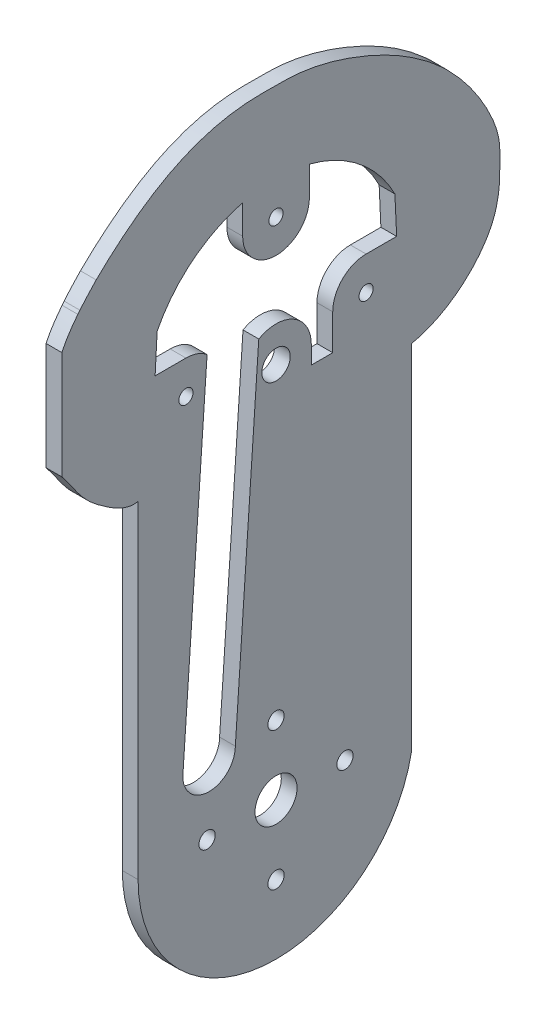
SolidWorks part; units mm, degrees
ref_plane "Plan de face" through (0, 0, 0) normal (0, 0, 1) x (1, 0, 0)
ref_plane "Plan de dessus" through (0, 0, 0) normal (0, 1, 0) x (1, 0, 0)
ref_plane "Plan de droite" through (0, 0, 0) normal (1, 0, 0) x (0, 0, -1)
sketch "Esquisse1" plane through (0, 0, 0) normal (1, 0, 0) x (0, 0, -1)
  line L19 (-6.1849, 6.1035) -> (-6.1849, 11.6469)
  line L20 (6.5151, 6.1035) -> (6.5151, 11.6469)
  line L21 (-10.6299, -14.9225) -> (-10.6299, -21.6694)
  line L22 (-16.9799, -8.5725) -> (-22.849, -8.5725)
  line L23 (17.3101, -8.5725) -> (23.1259, -8.5725)
  line L24 (-40.6082, -16.1449) -> (-40.6083, -16.3483)
  line L25 (0.1651, -90) -> (0.1651, -116.2575) construction
  line L26 (10.9601, -14.9225) -> (10.9601, -21.6694)
  line L27 (0.1651, 0) -> (0.1651, -90) construction
  line L28 (-26.0924, -27.6543) -> (-26.0924, -90) construction
  line L29 (10.9601, -21.6694) -> (6.8802, -21.6694)
  line L30 (6.8802, -21.6694) -> (6.8802, -18.2245)
  line L31 (-6.55, -18.2245) -> (-6.55, -21.6694)
  line L32 (-6.55, -21.6694) -> (-10.6299, -21.6694)
  line L33 (-26.0924, -90) -> (25.954, -90) construction
  line L34 (25.954, -90) -> (25.954, -27.6542) construction
  line L35 (-40.6082, 4.1425) -> (-40.6082, -12.7)
  line L36 (-26.0924, -27.6543) -> (-26.0924, -90)
  line L37 (25.954, -27.6542) -> (25.954, -90)
  line L38 (-40.6082, -16.1449) -> (-40.6082, -12.7)
  line L39 (-37.9035, 8.4934) -> (-36.4387, 10.3053) construction
  line L40 (-22.4631, -1.4086) -> (-22.849, -8.5725)
  line L41 (22.7933, -1.4086) -> (23.1259, -8.5725)
  circle A4 centre (-16.9799, -14.9225) radius 1.3525
  arc A5 (22.7933, -1.4086) -> (6.5151, 11.6469) centre (0.1651, -12.9465) ccw
  arc A6 (6.8802, -18.2245) -> (-6.55, -18.2245) centre (0.1651, -18.2245) ccw
  arc A7 (-37.1666, 9.4049) -> (-37.5578, 8.9143) centre (-0.9364, -19.8843) ccw
  circle A8 centre (0.1651, -18.2245) radius 2.7051
  circle A9 centre (17.3101, -14.9225) radius 1.3525
  circle A10 centre (0.1651, 6.1035) radius 1.3525
  arc A11 (-6.1849, 6.1035) -> (6.5151, 6.1035) centre (0.1651, 6.1035) ccw
  arc A12 (-6.1849, 11.6469) -> (-22.4631, -1.4086) centre (0.1651, -12.9465) ccw
  arc A13 (-10.6299, -14.9225) -> (-16.9799, -8.5725) centre (-16.9799, -14.9225) ccw
  arc A14 (-26.0924, -90) -> (25.954, -85.0614) centre (0.1651, -90) ccw
  arc A15 (17.3101, -8.5725) -> (10.9601, -14.9225) centre (17.3101, -14.9225) ccw
  circle A16 centre (0.1651, -103.1288) radius 1.55
  circle A17 centre (-12.9637, -90) radius 1.55
  circle A18 centre (0.1651, -76.8712) radius 1.55
  circle A19 centre (13.2939, -90) radius 1.55
  circle A20 centre (0.1651, -90) radius 4
  spline S5 degree 3 poles (31.4351, 15.2777) (30.2997, 16.3094) (29.1137, 17.2754) (26.6466, 19.0843) (25.3605, 19.9283) (21.4323, 22.2657) (18.7017, 23.5637) (14.4778, 25.2131) (13.0492, 25.7149) (10.8644, 26.3699) (10.1291, 26.5718) (8.6416, 26.9365) (7.8908, 27.0988) (5.638, 27.5124) (4.1274, 27.6937) (2.2253, 27.7687) (1.8441, 27.7755) (1.0809, 27.78) (0.6989, 27.7774) (-0.4463, 27.7791) (-1.2089, 27.7978) (-2.7327, 27.8153) (-3.4921, 27.8063) (-5.0041, 27.74) (-5.757, 27.6849) (-8.0062, 27.4518) (-9.4927, 27.2046) (-11.702, 26.6888) (-12.4349, 26.4915) (-13.8943, 26.0519) (-14.6221, 25.8075) (-16.7654, 25.0122) (-18.1515, 24.4005) (-20.8478, 23.0325) (-22.1587, 22.2775) (-24.7165, 20.6454) (-25.9664, 19.7652) (-28.3913, 17.9197) (-29.5674, 16.9543) (-31.2876, 15.4541) (-31.8538, 14.9457) (-32.9728, 13.9129) (-33.5258, 13.3888) (-34.0661, 12.8498) knots 0 0 0 0 0.0625 0.0625 0.125 0.125 0.25 0.25 0.3125 0.3125 0.34375 0.34375 0.375 0.375 0.4375 0.4375 0.453125 0.453125 0.46875 0.46875 0.5 0.5 0.53125 0.53125 0.5625 0.5625 0.625 0.625 0.65625 0.65625 0.6875 0.6875 0.75 0.75 0.8125 0.8125 0.875 0.875 0.9375 0.9375 0.96875 0.96875 1 1 1 1
  spline S6 degree 3 poles (-40.6083, -16.3483) (-40.3656, -16.6612) (-40.1123, -16.9655) (-39.6302, -17.5937) (-39.4007, -17.9172) (-38.719, -18.8931) (-38.2719, -19.5496) (-37.3385, -20.831) (-36.8555, -21.4585) (-36.0597, -22.3425) (-35.7819, -22.627) (-35.2029, -23.1772) (-34.9007, -23.4435) (-33.9719, -24.2127) (-33.3244, -24.6854) (-32.0108, -25.6045) (-31.3481, -26.0558) (-30.3031, -26.6606) (-29.9483, -26.8487) (-29.2225, -27.185) (-28.8514, -27.3338) (-28.0836, -27.5707) (-27.6853, -27.658) (-27.0907, -27.7154) (-26.8919, -27.7226) (-26.5928, -27.7129) (-26.493, -27.7063) (-26.293, -27.6856) (-26.1927, -27.6705) (-26.0924, -27.6543) knots 0 0 0 0 0.0625 0.0625 0.125 0.125 0.25 0.25 0.375 0.375 0.4375 0.4375 0.5 0.5 0.625 0.625 0.75 0.75 0.8125 0.8125 0.875 0.875 0.9375 0.9375 0.96875 0.96875 0.984375 0.984375 1 1 1 1
  spline S7 degree 3 poles (25.954, -27.6542) (27.1791, -27.4195) (28.3534, -27.0518) (30.0571, -26.3492) (30.6151, -26.0893) (31.7129, -25.5214) (32.2545, -25.2121) (33.8272, -24.2304) (34.814, -23.5021) (36.672, -21.9072) (37.5433, -21.0408) (38.7519, -19.6235) (39.1347, -19.135) (39.851, -18.1314) (40.1855, -17.6153) (40.8014, -16.5506) (41.0826, -16.002) (41.457, -15.1502) (41.5742, -14.8604) (41.7897, -14.2771) (41.888, -13.9835) (42.3347, -12.5068) (42.5462, -11.2963) (42.7176, -9.4515) (42.7506, -8.8307) (42.7729, -7.9005) (42.7754, -7.5904) (42.7756, -6.9702) (42.7721, -6.6601) (42.7721, -6.35) knots 0 0 0 0 0.125 0.125 0.1875 0.1875 0.25 0.25 0.375 0.375 0.5 0.5 0.5625 0.5625 0.625 0.625 0.6875 0.6875 0.71875 0.71875 0.75 0.75 0.875 0.875 0.9375 0.9375 0.96875 0.96875 1 1 1 1
  spline S8 degree 3 poles (42.7721, -6.35) (42.7721, -5.8749) (42.7838, -5.3981) (42.7897, -4.447) (42.7819, -3.973) (42.6725, -2.5632) (42.4992, -1.6375) (42.1063, -0.2679) (41.9541, 0.1856) (41.6148, 1.0877) (41.4301, 1.5303) (40.8449, 2.8393) (40.4166, 3.6895) (39.0468, 6.1905) (38.0131, 7.7873) (36.2917, 10.0821) (35.6885, 10.8307) (34.4365, 12.2817) (33.7862, 12.9857) (33.1121, 13.6686) knots 0 0 0 0 0.0625 0.0625 0.125 0.125 0.25 0.25 0.3125 0.3125 0.375 0.375 0.5 0.5 0.75 0.75 0.875 0.875 1 1 1 1
  spline S9 degree 3 poles (-37.5578, 8.9143) (-38.1429, 8.1702) (-38.7095, 7.4127) (-39.7419, 5.8248) (-40.2031, 4.9988) (-40.6082, 4.1425) knots 0 0 0 0 0.5 0.5 1 1 1 1
  spline S10 degree 3 poles (-34.0661, 12.8498) (-35.1598, 11.6922) (-36.2511, 10.5374) (-37.1666, 9.4049) knots 0 0 0 0 1 1 1 1
  spline S11 degree 2 poles (33.1121, 13.6686) (32.3322, 14.5391) (31.4351, 15.2777) knots 0 0 0 1 1 1
  point P69 (0.1651, -90)
  dimension "D2" = 4
  dimension "D3" = 8
  dimension "D4" = 3.1
  dimension "D1" = 90
sketch "Esquisse3" plane through (0, 0, 0) normal (1, 0, 0) x (0, 0, -1)
  line L0 (-6.1849, 6.1035) -> (-6.1849, 11.6469)
  line L1 (6.5151, 6.1035) -> (6.5151, 11.6469)
  line L3 (-16.9799, -8.5725) -> (-22.849, -8.5725)
  line L4 (17.3101, -8.5725) -> (23.1259, -8.5725)
  line L5 (-40.6082, -16.1449) -> (-40.6083, -16.3483)
  line L6 (0.1651, -90) -> (0.1651, -116.2575) construction
  line L7 (10.9601, -14.9225) -> (10.9601, -21.6694)
  line L8 (0.1651, 0) -> (0.1651, -90) construction
  line L9 (-26.0924, -27.6543) -> (-26.0924, -90) construction
  line L10 (10.9601, -21.6694) -> (6.8802, -21.6694)
  line L11 (6.8802, -21.6694) -> (6.8802, -18.2245)
  line L14 (-26.0924, -90) -> (25.954, -90) construction
  line L15 (25.954, -90) -> (25.954, -27.6542) construction
  line L16 (-40.6082, 4.1425) -> (-40.6082, -12.7)
  line L17 (-26.0924, -27.6543) -> (-26.0924, -90)
  line L18 (25.954, -27.6542) -> (25.954, -94.9386)
  line L19 (-40.6082, -16.1449) -> (-40.6082, -12.7)
  line L21 (-22.4631, -1.4086) -> (-22.849, -8.5725)
  line L22 (22.7933, -1.4086) -> (23.1259, -8.5725)
  line L23 (0.1651, -76.8533) -> (-12.9562, -90) construction
  line L24 (-6.3955, -83.4266) -> (-18.7628, -71.0833) construction
  line L25 (0.1651, -18.2245) -> (-16.9799, -14.9225) construction
  line L26 (-12.5792, -77.255) -> (-8.4074, -16.5735) construction
  line L27 (-10.4933, -46.9142) -> (-15.4698, -46.5721) construction
  line L28 (-17.5321, -76.5707) -> (-12.9562, -10.0101)
  line L29 (-7.5792, -77.255) -> (-3.1182, -12.3668)
  circle A0 centre (-16.9799, -14.9225) radius 1.3525
  arc A1 (22.7933, -1.4086) -> (6.5151, 11.6469) centre (0.1651, -12.9465) ccw
  arc A2 (6.8802, -18.2245) -> (-3.1182, -12.3668) centre (0.1651, -18.2245) ccw
  arc A3 (-37.1666, 9.4049) -> (-37.5578, 8.9143) centre (-0.9364, -19.8843) ccw
  circle A4 centre (0.1651, -18.2245) radius 2.7051
  circle A5 centre (17.3101, -14.9225) radius 1.3525
  circle A6 centre (0.1651, 6.1035) radius 1.3525
  arc A7 (-6.1849, 6.1035) -> (6.5151, 6.1035) centre (0.1651, 6.1035) ccw
  arc A8 (-6.1849, 11.6469) -> (-22.4631, -1.4086) centre (0.1651, -12.9465) ccw
  arc A9 (-12.9562, -10.0101) -> (-16.9799, -8.5725) centre (-16.9799, -14.9225) ccw
  arc A10 (-26.0924, -90) -> (25.954, -94.9386) centre (0.1651, -90) ccw
  arc A11 (17.3101, -8.5725) -> (10.9601, -14.9225) centre (17.3101, -14.9225) ccw
  circle A12 centre (0.1651, -103.1288) radius 1.55
  circle A13 centre (-12.9562, -90) radius 1.55
  circle A14 centre (0.1651, -76.8533) radius 1.55
  circle A15 centre (13.2939, -90) radius 1.55
  circle A16 centre (0.1651, -90) radius 4
  circle A17 centre (0.1651, -90) radius 26.2575 construction
  arc A18 (-17.5321, -76.5707) -> (-7.5792, -77.255) centre (-12.5792, -77.255) ccw
  spline S0 degree 3 poles (31.4351, 15.2777) (30.2997, 16.3094) (29.1137, 17.2754) (26.6466, 19.0843) (25.3605, 19.9283) (21.4323, 22.2657) (18.7017, 23.5637) (14.4778, 25.2131) (13.0492, 25.7149) (10.8644, 26.3699) (10.1291, 26.5718) (8.6416, 26.9365) (7.8908, 27.0988) (5.638, 27.5124) (4.1274, 27.6937) (2.2253, 27.7687) (1.8441, 27.7755) (1.0809, 27.78) (0.6989, 27.7774) (-0.4463, 27.7791) (-1.2089, 27.7978) (-2.7327, 27.8153) (-3.4921, 27.8063) (-5.0041, 27.74) (-5.757, 27.6849) (-8.0062, 27.4518) (-9.4927, 27.2046) (-11.702, 26.6888) (-12.4349, 26.4915) (-13.8943, 26.0519) (-14.6221, 25.8075) (-16.7654, 25.0122) (-18.1515, 24.4005) (-20.8478, 23.0325) (-22.1587, 22.2775) (-24.7165, 20.6454) (-25.9664, 19.7652) (-28.3913, 17.9197) (-29.5674, 16.9543) (-31.2876, 15.4541) (-31.8538, 14.9457) (-32.9728, 13.9129) (-33.5258, 13.3888) (-34.0661, 12.8498) knots 0 0 0 0 0.0625 0.0625 0.125 0.125 0.25 0.25 0.3125 0.3125 0.34375 0.34375 0.375 0.375 0.4375 0.4375 0.453125 0.453125 0.46875 0.46875 0.5 0.5 0.53125 0.53125 0.5625 0.5625 0.625 0.625 0.65625 0.65625 0.6875 0.6875 0.75 0.75 0.8125 0.8125 0.875 0.875 0.9375 0.9375 0.96875 0.96875 1 1 1 1
  spline S1 degree 3 poles (-40.6082, -16.3483) (-40.3656, -16.6612) (-40.1123, -16.9655) (-39.6302, -17.5937) (-39.4007, -17.9172) (-38.719, -18.8931) (-38.2719, -19.5496) (-37.3385, -20.831) (-36.8555, -21.4585) (-36.0597, -22.3425) (-35.7819, -22.627) (-35.2029, -23.1772) (-34.9007, -23.4435) (-33.9719, -24.2127) (-33.3244, -24.6854) (-32.0108, -25.6045) (-31.3481, -26.0558) (-30.3031, -26.6606) (-29.9483, -26.8487) (-29.2225, -27.185) (-28.8514, -27.3338) (-28.0836, -27.5707) (-27.6853, -27.658) (-27.0907, -27.7154) (-26.8919, -27.7226) (-26.5928, -27.7129) (-26.493, -27.7063) (-26.293, -27.6856) (-26.1927, -27.6705) (-26.0924, -27.6543) knots 0 0 0 0 0.0625 0.0625 0.125 0.125 0.25 0.25 0.375 0.375 0.4375 0.4375 0.5 0.5 0.625 0.625 0.75 0.75 0.8125 0.8125 0.875 0.875 0.9375 0.9375 0.96875 0.96875 0.984375 0.984375 1 1 1 1
  spline S2 degree 3 poles (25.954, -27.6542) (27.1791, -27.4195) (28.3534, -27.0518) (30.0571, -26.3492) (30.6151, -26.0893) (31.7129, -25.5214) (32.2545, -25.2121) (33.8272, -24.2304) (34.814, -23.5021) (36.672, -21.9072) (37.5433, -21.0408) (38.7519, -19.6235) (39.1347, -19.135) (39.851, -18.1314) (40.1855, -17.6153) (40.8014, -16.5506) (41.0826, -16.002) (41.457, -15.1502) (41.5742, -14.8604) (41.7897, -14.2771) (41.888, -13.9835) (42.3347, -12.5068) (42.5462, -11.2963) (42.7176, -9.4515) (42.7506, -8.8307) (42.7729, -7.9005) (42.7754, -7.5904) (42.7756, -6.9702) (42.7721, -6.6601) (42.7721, -6.35) knots 0 0 0 0 0.125 0.125 0.1875 0.1875 0.25 0.25 0.375 0.375 0.5 0.5 0.5625 0.5625 0.625 0.625 0.6875 0.6875 0.71875 0.71875 0.75 0.75 0.875 0.875 0.9375 0.9375 0.96875 0.96875 1 1 1 1
  spline S3 degree 3 poles (42.7721, -6.35) (42.7721, -5.8749) (42.7838, -5.3981) (42.7897, -4.447) (42.7819, -3.973) (42.6725, -2.5632) (42.4992, -1.6375) (42.1063, -0.2679) (41.9541, 0.1856) (41.6148, 1.0877) (41.4301, 1.5303) (40.8449, 2.8393) (40.4166, 3.6895) (39.0468, 6.1905) (38.0131, 7.7873) (36.2917, 10.0821) (35.6885, 10.8307) (34.4365, 12.2817) (33.7862, 12.9857) (33.1121, 13.6686) knots 0 0 0 0 0.0625 0.0625 0.125 0.125 0.25 0.25 0.3125 0.3125 0.375 0.375 0.5 0.5 0.75 0.75 0.875 0.875 1 1 1 1
  spline S4 degree 3 poles (-37.5578, 8.9143) (-38.1429, 8.1702) (-38.7095, 7.4127) (-39.7419, 5.8248) (-40.2031, 4.9988) (-40.6082, 4.1425) knots 0 0 0 0 0.5 0.5 1 1 1 1
  spline S5 degree 3 poles (-34.0661, 12.8498) (-35.1598, 11.6922) (-36.2511, 10.5374) (-37.1666, 9.4049) knots 0 0 0 0 1 1 1 1
  spline S6 degree 2 poles (33.1121, 13.6686) (32.3322, 14.5391) (31.4351, 15.2777) knots 0 0 0 1 1 1
  point P57 (0.1651, -90)
  dimension "D2" = 8
  dimension "D3" = 3.1
  dimension "D4" = 10
  dimension "D1" = 90
extrude "Boss.-Extru.2" add sketch "Esquisse3" along normal blind 3
